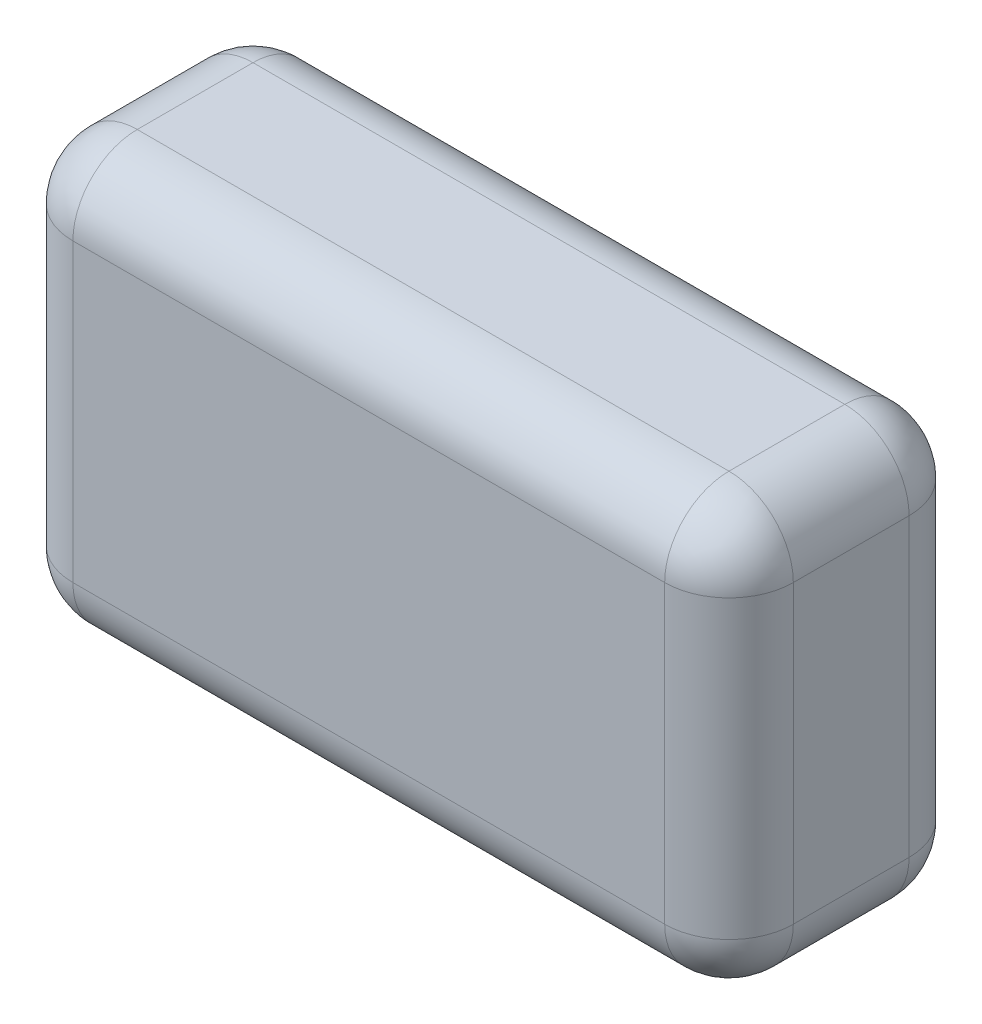
SolidWorks part; units mm, degrees
material "ABS"
ref_plane "Front Plane" through (0, 0, 0) normal (0, 0, 1) x (1, 0, 0)
ref_plane "Top Plane" through (0, 0, 0) normal (0, 1, 0) x (1, 0, 0)
ref_plane "Right Plane" through (0, 0, 0) normal (1, 0, 0) x (0, 0, -1)
sketch "Sketch1" plane through (0, 0, 0) normal (0, 0, 1) x (1, 0, 0)
  line L1 (-46, 33) -> (46, 33)
  line L2 (-56, 23) -> (-56, -23)
  line L3 (-46, -33) -> (46, -33)
  line L4 (56, 23) -> (56, -23)
  line L5 (-56, 33) -> (56, -33) construction
  line L6 (-56, -33) -> (56, 33) construction
  arc A0 (46, 33) -> (56, 23) centre (46, 23) cw
  arc A1 (56, -23) -> (46, -33) centre (46, -23) cw
  arc A2 (-46, -33) -> (-56, -23) centre (-46, -23) cw
  arc A3 (-46, 33) -> (-56, 23) centre (-46, 23) ccw
  point P0 (0, 0)
  dimension "D1" = 10
  dimension "D2" = 66
  dimension "D3" = 112
extrude "Boss-Extrude1" add sketch "Sketch1" along normal blind 38
fillet "Fillet1" radius 10 16 edges at (53.0711, 30.0711, 0) (53.0711, -30.0711, 0) (-53.0711, -30.0711, 0) (-53.0711, 30.0711, 0) (-56, 0, 0) (0, 33, 0) (56, 0, 0) (0, -33, 0) (56, 0, 38) (53.0711, -30.0711, 38) (0, -33, 38) (-53.0711, -30.0711, 38) (-56, 0, 38) (-53.0711, 30.0711, 38) (0, 33, 38) (53.0711, 30.0711, 38)
